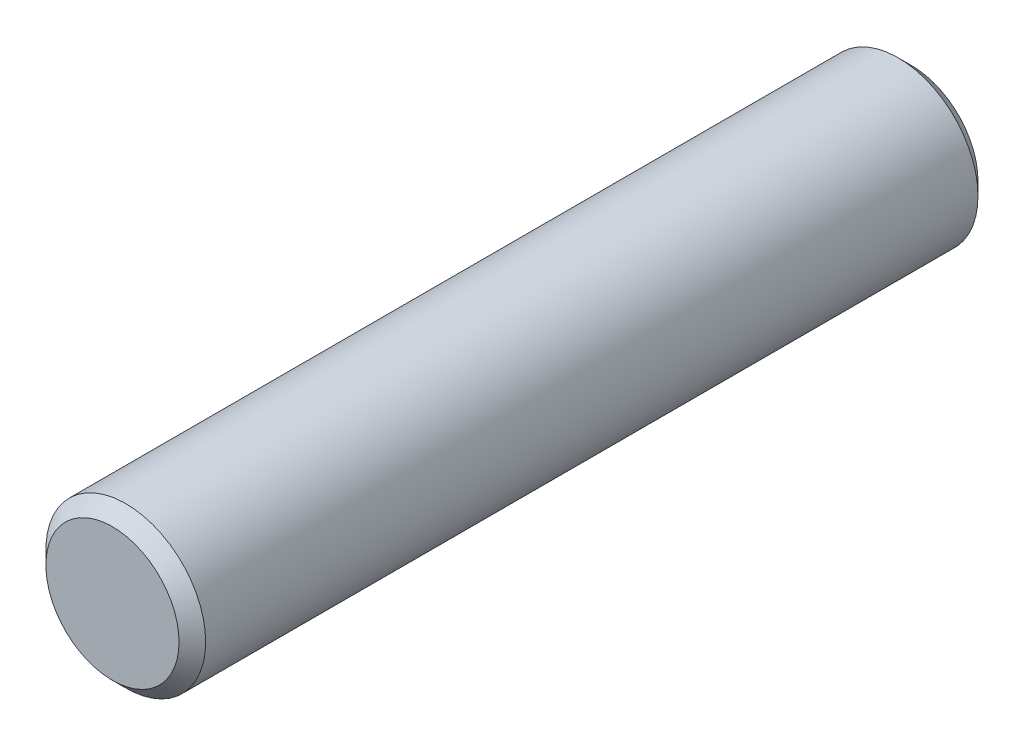
SolidWorks part; units mm, degrees
ref_plane "Front Plane" through (0, 0, 0) normal (0, 0, 1) x (1, 0, 0)
ref_plane "Top Plane" through (0, 0, 0) normal (0, 1, 0) x (1, 0, 0)
ref_plane "Right Plane" through (0, 0, 0) normal (1, 0, 0) x (0, 0, -1)
sketch "Sketch1" plane through (0, 0, 0) normal (0, 0, 1) x (1, 0, 0)
  circle A0 centre (0, 0) radius 3
  dimension "D1" = 6
extrude "Boss-Extrude1" add sketch "Sketch1" along normal mid plane 30 contours A0
chamfer "Chamfer1" distance 0.5 angle 45 2 edges at (3, 0, -15) (3, 0, 15)
